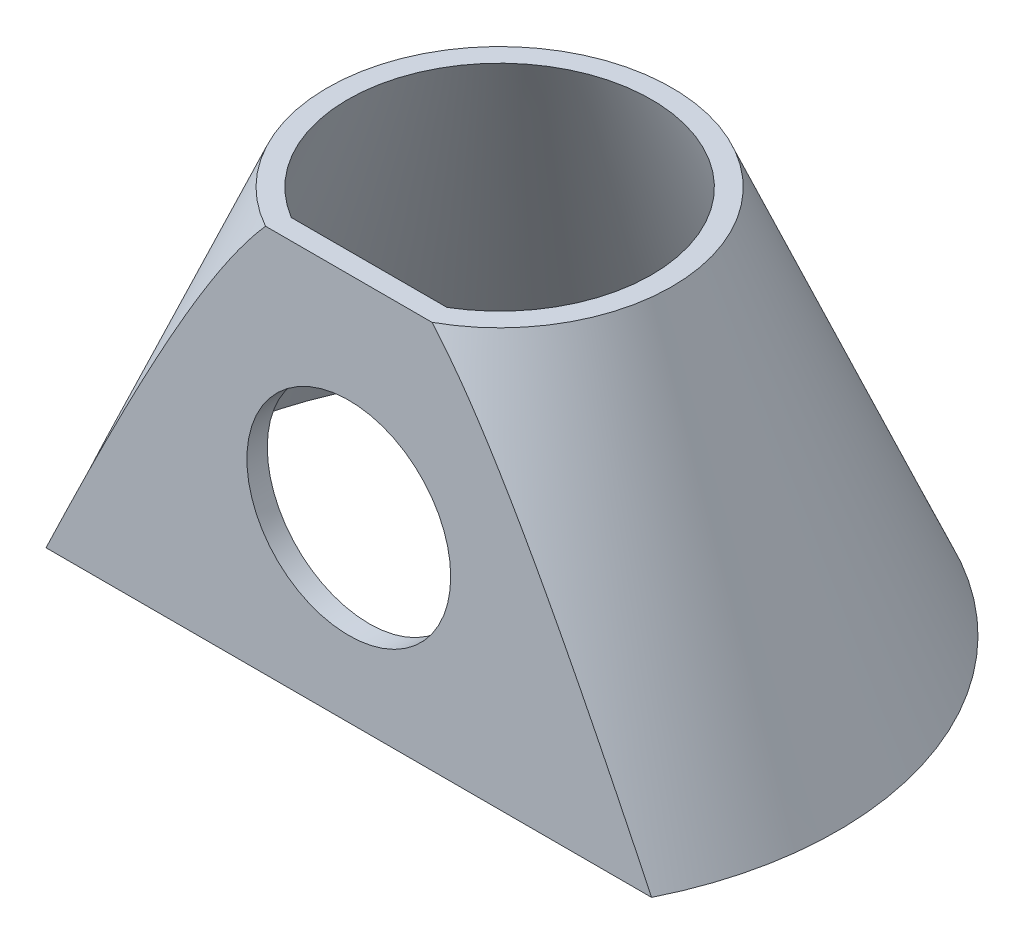
SolidWorks part; units mm, degrees
ref_plane "Front Plane" through (0, 0, 0) normal (0, 0, 1) x (1, 0, 0)
ref_plane "Top Plane" through (0, 0, 0) normal (0, 1, 0) x (1, 0, 0)
ref_plane "Right Plane" through (0, 0, 0) normal (1, 0, 0) x (0, 0, -1)
sketch "Sketch3" plane through (0, 0, 0) normal (0, 0, 1) x (1, 0, 0)
  line L0 (0, 50) -> (0, -2.1681) construction
  line L1 (-7.025, 18.3667) -> (-8.025, 18.3667)
  line L2 (-8.025, 18.3667) -> (-17.025, -2.6833)
  line L3 (-17.025, -2.6833) -> (-16.025, -2.6833)
  line L4 (-16.025, -2.6833) -> (-7.025, 18.3667)
  dimension "D1" = 1
  dimension "D2" = 1
  dimension "D3" = 21.05
  dimension "D4" = 50
  dimension "D5" = 8.025
  dimension "D6" = 9
revolve "Revolve1" add sketch "Sketch3" angle 360 about L0
sketch "Sketch4" plane through (0, 18.3667, 0) normal (0, 1, 0) x (1, 0, 0)
  line L1 (-21.6652, -7.4) -> (23.1057, -7.4)
  line L2 (-21.6652, -7.4) -> (-21.6652, -18.0904)
  line L3 (-21.6652, -18.0904) -> (23.1057, -18.0904)
  line L4 (23.1057, -7.4) -> (23.1057, -18.0904)
  dimension "D1" = 7.4
extrude "Cut-Extrude1" cut sketch "Sketch4" against normal through all both and the other way through all
sketch "Sketch6" plane through (0, -2.6833, 0) normal (0, -1, 0) x (1, 0, 0)
  line L1 (-15.3327, 7.4) -> (15.3327, 7.4)
  line L2 (-15.3327, 7.4) -> (-15.3327, 6.4)
  line L3 (-15.3327, 6.4) -> (15.3327, 6.4)
  line L4 (15.3327, 7.4) -> (15.3327, 6.4)
  dimension "D1" = 1
  dimension "D2" = 0
extrude "Boss-Extrude1" add sketch "Sketch6" against normal up to surface (21.05 mm away) up to face at (0, 18.3667, -0.3125)
sketch "Sketch7" plane through (0, 0, 0) normal (1, 0, 0) x (0, 0, -1)
  line L0 (0, 14.9308) -> (0, -7.3857) construction
  line L1 (8.025, 18.3667) -> (17.025, -2.6833)
  line L2 (17.025, -2.6833) -> (18.6003, -2.6833)
  line L3 (8.025, 18.3667) -> (18.6003, 18.3667)
  line L4 (18.6003, 18.3667) -> (18.6003, -2.6833)
  point P7 (17.025, -2.6833)
revolve "Cut-Revolve1" cut sketch "Sketch7" angle 360 about L0
sketch "Sketch8" plane through (0, 18.3667, 0) normal (0, 1, 0) x (1, 0, 0)
  line L1 (-24.5955, 17.4568) -> (19.4181, 17.4568)
  line L2 (-24.5955, 17.4568) -> (-24.5955, -8.7983)
  line L3 (-24.5955, -8.7983) -> (19.4181, -8.7983)
  line L4 (19.4181, 17.4568) -> (19.4181, -8.7983)
extrude "Cut-Extrude2" cut sketch "Sketch8" against normal blind 1
sketch "Sketch9" plane through (0, -2.6833, 0) normal (0, -1, 0) x (1, 0, 0)
  line L1 (26.2277, 11.568) -> (-24.5887, 11.568)
  line L2 (26.2277, 11.568) -> (26.2277, -18.9809)
  line L3 (26.2277, -18.9809) -> (-24.5887, -18.9809)
  line L4 (-24.5887, 11.568) -> (-24.5887, -18.9809)
extrude "Cut-Extrude3" cut sketch "Sketch9" against normal blind 1
sketch "Sketch10" plane through (0, 0, 7.4) normal (0, 0, 1) x (1, 0, 0)
  line L1 (-4.0848, 17.3667) -> (4.0848, 17.3667) construction
  line L2 (-14.8565, -1.6833) -> (14.8565, -1.6833) construction
  circle A0 centre (0, 7.0167) radius 5
other "AlignGroup1" parameters "D1"=7.6762, "D2"=6.9693, "D3"=10.35, "D4"=19.05
extrude "Cut-Extrude4" cut sketch "Sketch10" against normal up to next
